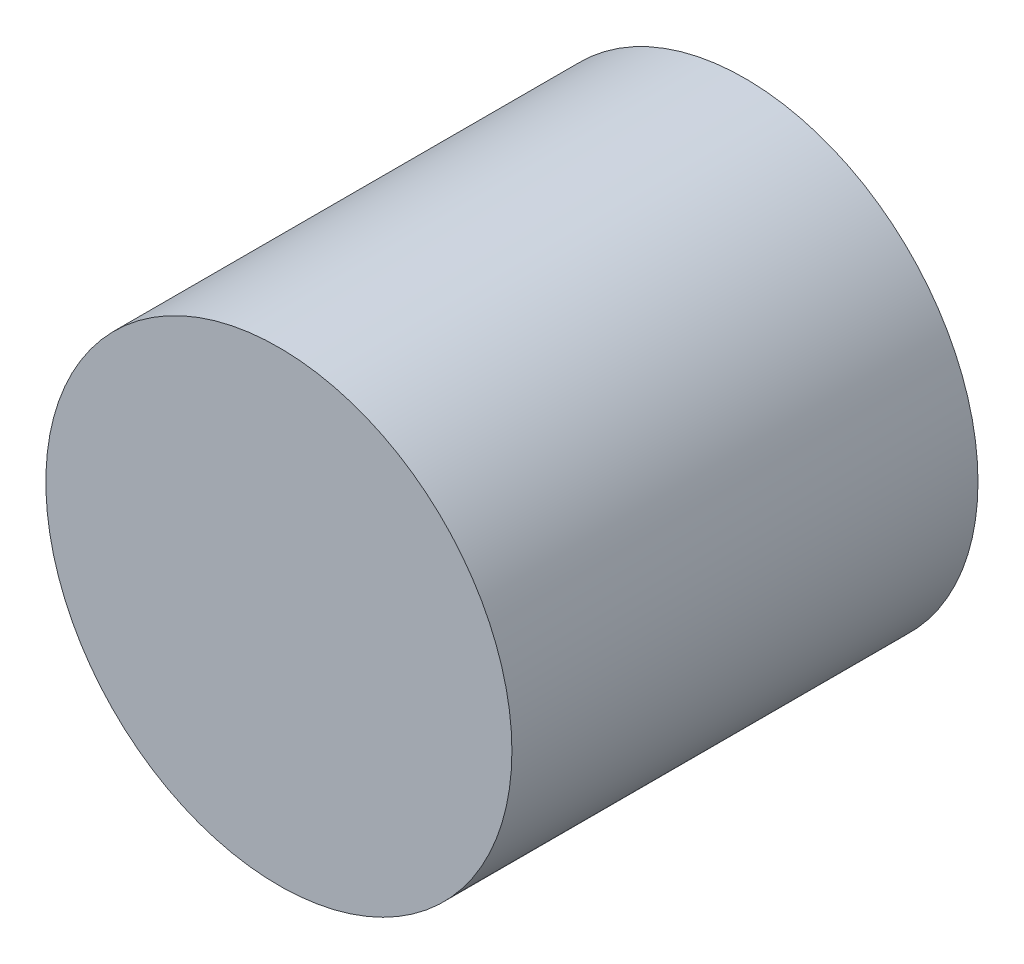
SolidWorks part; units mm, degrees
ref_plane "Front Plane" through (0, 0, 0) normal (0, 0, 1) x (1, 0, 0)
ref_plane "Top Plane" through (0, 0, 0) normal (0, 1, 0) x (1, 0, 0)
ref_plane "Right Plane" through (0, 0, 0) normal (1, 0, 0) x (0, 0, -1)
sketch "Sketch1" plane through (0, 0, 0) normal (0, 0, 1) x (1, 0, 0)
  circle A0 centre (0, 0) radius 7.5
  dimension "D1" = 15
extrude "Boss-Extrude1" add sketch "Sketch1" along normal blind 15
